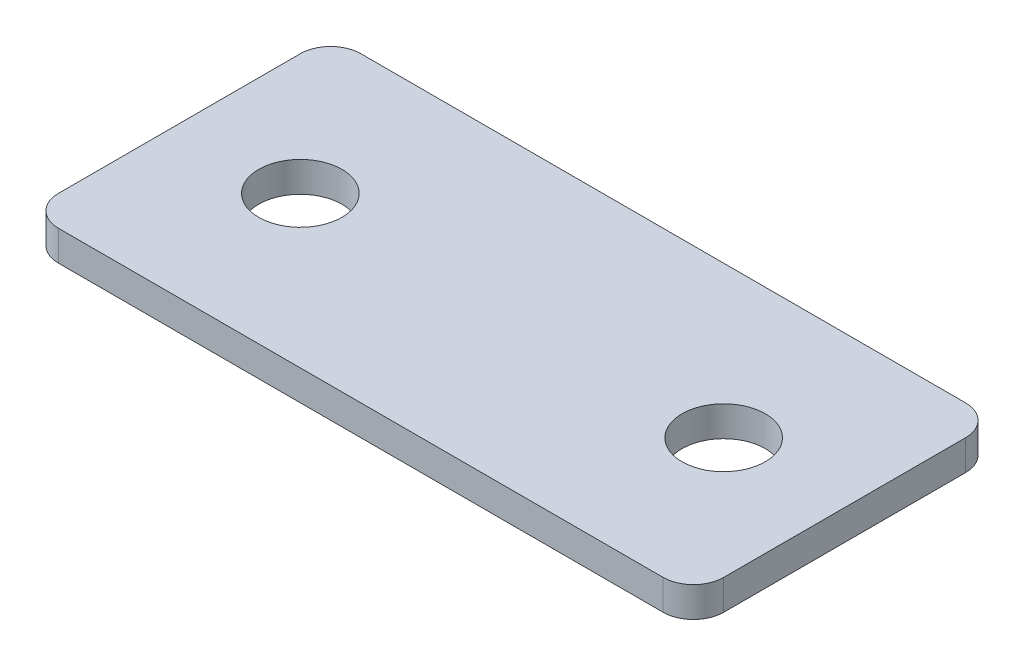
SolidWorks part; units mm, degrees
material "Plain Carbon Steel"
ref_plane "Front" through (0, 0, 0) normal (0, 0, 1) x (1, 0, 0)
ref_plane "Top" through (0, 0, 0) normal (0, 1, 0) x (1, 0, 0)
ref_plane "Right" through (0, 0, 0) normal (1, 0, 0) x (0, 0, -1)
sketch "Sketch1" plane through (0, 0, 0) normal (0, 1, 0) x (1, 0, 0)
  line L0 (34.925, 31.75) -> (34.925, 0) construction
  line L1 (0, 0) -> (69.85, 0)
  line L2 (0, 0) -> (0, 31.75)
  line L3 (0, 31.75) -> (69.85, 31.75)
  line L4 (69.85, 0) -> (69.85, 31.75)
  line L5 (12.7, 15.875) -> (57.15, 15.875) construction
  circle A0 centre (12.7, 15.875) radius 4.3688
  circle A1 centre (57.15, 15.875) radius 4.3688
  point P10 (34.925, 15.875)
  dimension "D4" = 8.7376
  dimension "D1" = 44.45
  dimension "D2" = 31.75
  dimension "D3" = 69.85
extrude "Boss-Extrude1" add sketch "Sketch1" along normal blind 3.175
fillet "Fillet1" radius 3.175 4 edges at (0, 1.5875, -31.75) (0, 1.5875, 0) (69.85, 1.5875, -31.75) (69.85, 1.5875, 0)
